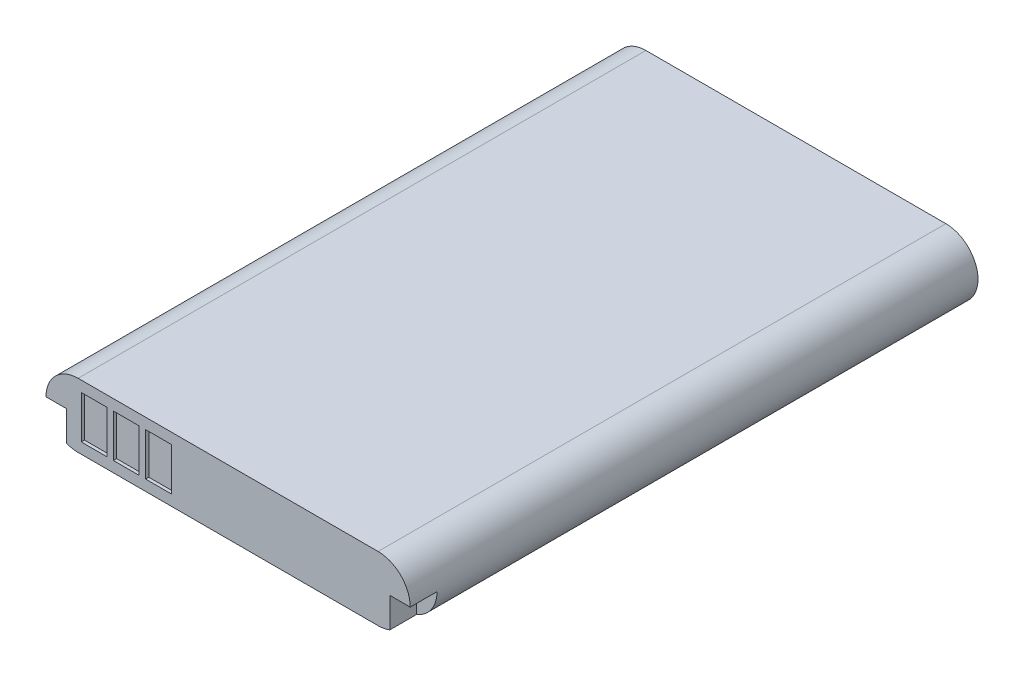
SolidWorks part; units mm, degrees
ref_plane "Front Plane" through (0, 0, 0) normal (0, 0, 1) x (1, 0, 0)
ref_plane "Top Plane" through (0, 0, 0) normal (0, 1, 0) x (1, 0, 0)
ref_plane "Right Plane" through (0, 0, 0) normal (1, 0, 0) x (0, 0, -1)
sketch "Sketch1" plane through (0, 0, 0) normal (0, 0, 1) x (1, 0, 0)
  line L0 (-14, 0) -> (14, 0) construction
  line L1 (-14, 3) -> (14, 3)
  line L2 (-14, -3) -> (14, -3)
  arc A0 (-14, 3) -> (-14, -3) centre (-14, 0) ccw
  arc A1 (14, -3) -> (14, 3) centre (14, 0) ccw
  point P3 (0, 0)
  point P8 (-17, 0)
  point P9 (17, 0)
  dimension "D1" = 6
  dimension "D2" = 34
extrude "Boss-Extrude1" add sketch "Sketch1" along normal blind 53
sketch "Sketch2" plane through (0, 0, 53) normal (0, 0, 1) x (1, 0, 0)
  line L0 (-11.3, 0) -> (0, 0) construction
  line L1 (-13.7, 2) -> (-11.3, 2)
  line L2 (-13.7, 2) -> (-13.7, -2)
  line L3 (-13.7, -2) -> (-11.3, -2)
  line L4 (-11.3, 2) -> (-11.3, -2)
  line L5 (-8.3, 2) -> (-8.3, -2)
  line L6 (-10.7, -2) -> (-8.3, -2)
  line L7 (-10.7, 2) -> (-10.7, -2)
  line L8 (-10.7, 2) -> (-8.3, 2)
  line L9 (-5.3, 2) -> (-5.3, -2)
  line L10 (-7.7, -2) -> (-5.3, -2)
  line L11 (-7.7, 2) -> (-7.7, -2)
  line L12 (-7.7, 2) -> (-5.3, 2)
  arc A0 (-14, 3) -> (-14, -3) centre (-14, 0) ccw construction
  point P5 (-12.5, -2)
  point P18 (-17, 0)
  point P19 (-12.5, 2)
  point P22 (-9.5, -2)
  dimension "D1" = 4
  dimension "D2" = 4.5
  dimension "D3" = 2.4
  dimension "D5" = 3
  dimension "D4" = 3
extrude "Cut-Extrude1" cut sketch "Sketch2" against normal blind 0.3
sketch "Sketch3" plane through (0, 0, 53) normal (0, 0, 1) x (1, 0, 0)
  line L0 (0, 0) -> (0, -3) construction
  line L1 (-19.1, 0) -> (-15.1, 0)
  line L2 (-19.1, 0) -> (-19.1, -4)
  line L3 (-19.1, -4) -> (-15.1, -4)
  line L4 (-15.1, 0) -> (-15.1, -4)
  line L5 (-14, -3) -> (14, -3) construction
  line L6 (19.1, 0) -> (15.1, 0)
  line L7 (19.1, 0) -> (19.1, -4)
  line L8 (19.1, -4) -> (15.1, -4)
  line L9 (15.1, 0) -> (15.1, -4)
  arc A0 (-14, 3) -> (-14, -3) centre (-14, 0) ccw construction
  point P7 (-17, 0)
  dimension "D1" = 30.2
  dimension "D2" = 4
extrude "Cut-Extrude2" cut sketch "Sketch3" against normal blind 2.5
